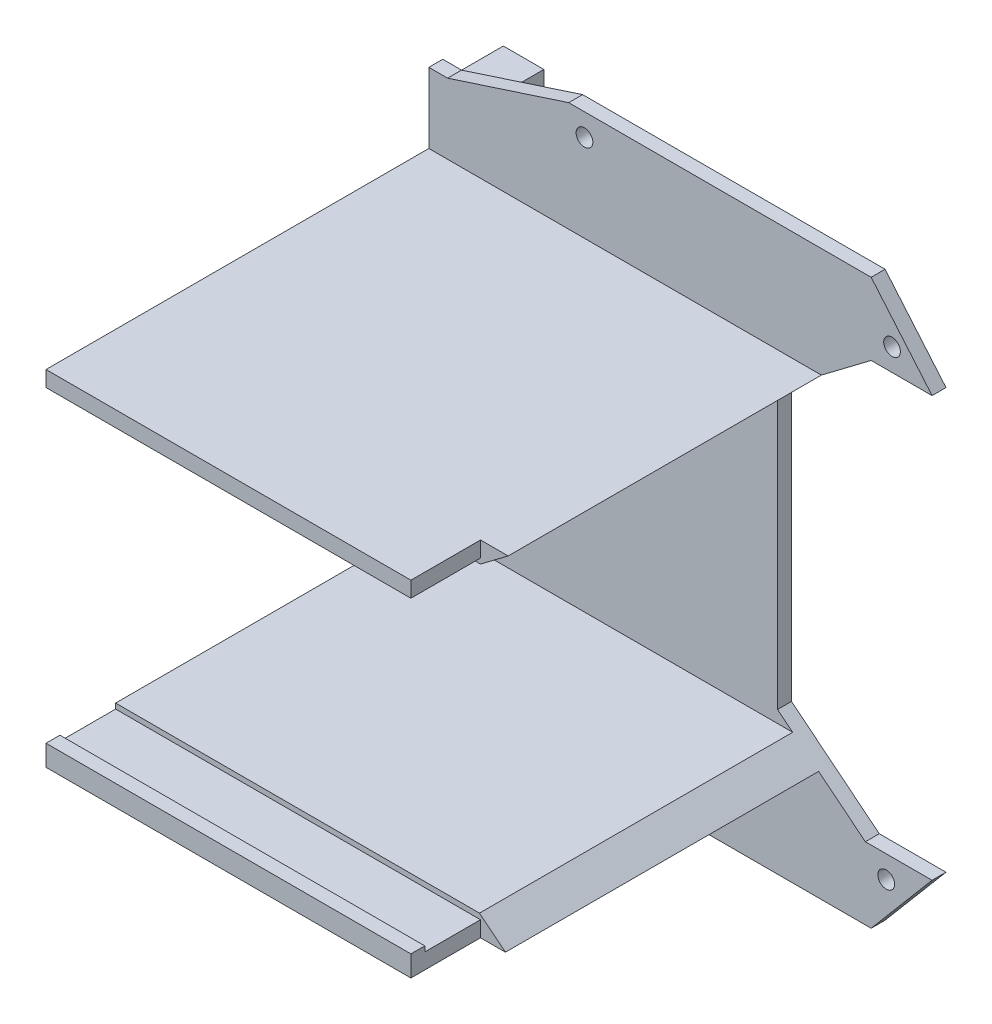
SolidWorks part; units mm, degrees
ref_plane "前视基准面" through (0, 0, 0) normal (0, 0, 1) x (1, 0, 0)
ref_plane "上视基准面" through (0, 0, 0) normal (0, 1, 0) x (1, 0, 0)
ref_plane "右视基准面" through (0, 0, 0) normal (1, 0, 0) x (0, 0, -1)
other "Configuration Table"
sketch "草图1" plane through (0, 0, 0) normal (0, 0, 1) x (1, 0, 0)
  line L0 (-117.8959, 10.15) -> (-117.8959, 50.15) construction
  line L1 (-117.8959, 10.15) -> (-117.8959, 50.15)
  line L3 (-104.45, 60.3) -> (-117.8959, 50.15)
  line L4 (-117.8959, 10.15) -> (-105.2853, 0)
  line L5 (-165.3, 65) -> (-168, 65)
  line L6 (-168, 65) -> (-168, -4.7)
  line L11 (-104.45, 68.85) -> (-104.45, 60.3)
  line L12 (-104.45, 60.3) -> (-95.7, 60.3)
  line L13 (-95.7, 60.3) -> (-104.45, 70.65)
  line L14 (-104.45, 70.65) -> (-147.9, 70.65)
  line L15 (-147.9, 70.65) -> (-165.3, 65)
  line L16 (-165.3, 65) -> (-159.4717, 65)
  line L17 (-159.4717, 65) -> (-149.4421, 68.2567)
  line L18 (-149.4421, 68.2567) -> (-149.4421, 63.85)
  line L19 (-149.4421, 63.85) -> (-141.4421, 63.85)
  line L20 (-141.4421, 63.85) -> (-141.4421, 68.85)
  line L21 (-141.4421, 68.85) -> (-104.45, 68.85)
  line L22 (-104.45, 68.85) -> (-104.45, 60.3)
  line L23 (-104.45, 60.3) -> (-95.7, 60.3)
  line L24 (-95.7, 60.3) -> (-104.45, 70.65)
  line L25 (-104.45, 70.65) -> (-147.9, 70.65)
  line L26 (-147.9, 70.65) -> (-165.3, 65)
  line L27 (-165.3, 65) -> (-159.4717, 65)
  line L28 (-159.4717, 65) -> (-149.4421, 68.2567)
  line L29 (-149.4421, 68.2567) -> (-149.4421, 63.85)
  line L30 (-149.4421, 63.85) -> (-141.4421, 63.85)
  line L31 (-141.4421, 63.85) -> (-141.4421, 68.85)
  line L32 (-141.4421, 68.85) -> (-104.45, 68.85)
  line L36 (-141.1744, -8.55) -> (-145.1744, -14.55)
  line L37 (-145.1744, -14.55) -> (-161.298, -14.55)
  line L38 (-161.298, -14.55) -> (-164.1652, -8.55)
  line L39 (-164.1652, -8.55) -> (-165.3, -8.55)
  line L40 (-165.3, -8.55) -> (-165.3, -4.7)
  line L41 (-165.3, -4.7) -> (-168, -4.7)
  line L42 (-168, -4.7) -> (-162.4327, -16.35)
  line L43 (-162.4327, -16.35) -> (-141.1744, -16.35)
  line L44 (-141.1744, -16.35) -> (-137.1744, -10.35)
  line L45 (-137.1744, -10.35) -> (-104.45, -10.35)
  line L46 (-104.45, -10.35) -> (-95.7, 0)
  line L47 (-95.7, 0) -> (-105.2853, 0)
  line L48 (-105.2853, 0) -> (-105.2853, -8.55)
  line L49 (-105.2853, -8.55) -> (-141.1744, -8.55)
  line L50 (-141.1744, -8.55) -> (-145.1744, -14.55)
  line L51 (-145.1744, -14.55) -> (-161.298, -14.55)
  line L52 (-161.298, -14.55) -> (-164.1652, -8.55)
  line L53 (-164.1652, -8.55) -> (-165.3, -8.55)
  line L54 (-165.3, -8.55) -> (-165.3, -4.7)
  line L55 (-165.3, -4.7) -> (-168, -4.7)
  line L56 (-168, -4.7) -> (-162.4327, -16.35)
  line L57 (-162.4327, -16.35) -> (-141.1744, -16.35)
  line L58 (-141.1744, -16.35) -> (-137.1744, -10.35)
  line L59 (-137.1744, -10.35) -> (-104.45, -10.35)
  line L60 (-104.45, -10.35) -> (-95.7, 0)
  line L61 (-95.7, 0) -> (-105.2853, 0)
  line L62 (-105.2853, 0) -> (-105.2853, -8.55)
  line L63 (-105.2853, -8.55) -> (-141.1744, -8.55)
  circle A0 centre (-145.6421, 67.45) radius 1.2 construction
  circle A1 centre (-145.6421, 67.45) radius 1.2
  circle A2 centre (-101.45, 63.5) radius 1.2 construction
  circle A3 centre (-101.45, 63.5) radius 1.2
  circle A4 centre (-102.2853, -3.2) radius 1.2 construction
  circle A5 centre (-102.2853, -3.2) radius 1.2
  circle A6 centre (-140.9744, -12.15) radius 1.2 construction
  circle A7 centre (-140.9744, -12.15) radius 1.2
  dimension "D1" = 0
  dimension "D2" = 0
extrude "凸台-拉伸1" add sketch "草图1" along normal blind 2 contours L63 L62 L4 L1 L3 L22 L32 L31 L30 L29 L28 L27 L5 L6 L55 L54 L53 L52 L51 L50 | L31 L32 L22 L23 L24 L25 L26 L27 L28 L29 L30 A3 A1 | L62 L63 L50 L51 L52 L53 L54 L55 L56 L57 L58 L59 L60 L61 A7 A5
sketch "草图2" plane through (0, 0, 0) normal (0, 0, -1) x (-1, 0, 0)
  line L0 (165.3, 65) -> (165.3, 59) construction
  line L1 (165.3, 65) -> (165.3, 59)
  line L2 (165.3, 1.3) -> (165.3, -4.7) construction
  line L3 (165.3, 1.3) -> (165.3, -4.7)
  line L4 (165.3, 59) -> (150.9, 59) construction
  line L5 (165.3, 59) -> (150.9, 59)
  line L6 (165.3, 1.3) -> (150.9, 1.3) construction
  line L7 (165.3, 1.3) -> (150.9, 1.3)
  line L8 (165.3, 59) -> (150.9, 59)
  line L10 (165.3, 65) -> (159.4717, 65)
  line L11 (165.3, 65) -> (165.3, 59)
  line L12 (165.3, 59) -> (159.4717, 59)
  line L13 (159.4717, 65) -> (159.4717, 59)
  line L14 (165.3, 1.3) -> (159.4717, 1.3)
  line L15 (104.45, 60.3) -> (117.8959, 50.15)
  line L16 (117.8959, 50.15) -> (117.8959, 10.15)
  line L17 (117.8959, 10.15) -> (105.2853, 0)
  line L18 (105.2853, 0) -> (95.7, 0)
  line L19 (95.7, 0) -> (104.45, -10.35)
  line L20 (104.45, -10.35) -> (137.1744, -10.35)
  line L21 (137.1744, -10.35) -> (141.1744, -16.35)
  line L22 (141.1744, -16.35) -> (162.4327, -16.35)
  line L23 (162.4327, -16.35) -> (168, -4.7)
  line L24 (168, -4.7) -> (168, 65)
  line L25 (168, 65) -> (165.3, 65)
  line L26 (165.3, 65) -> (147.9, 70.65)
  line L27 (147.9, 70.65) -> (104.45, 70.65)
  line L28 (104.45, 70.65) -> (95.7, 60.3)
  line L29 (95.7, 60.3) -> (104.45, 60.3)
  line L30 (104.45, 60.3) -> (117.8959, 50.15)
  line L31 (117.8959, 50.15) -> (117.8959, 10.15)
  line L32 (117.8959, 10.15) -> (105.2853, 0)
  line L33 (105.2853, 0) -> (95.7, 0)
  line L34 (95.7, 0) -> (104.45, -10.35)
  line L35 (104.45, -10.35) -> (137.1744, -10.35)
  line L36 (137.1744, -10.35) -> (141.1744, -16.35)
  line L37 (141.1744, -16.35) -> (162.4327, -16.35)
  line L38 (162.4327, -16.35) -> (168, -4.7)
  line L39 (168, -4.7) -> (168, 65)
  line L40 (168, 65) -> (165.3, 65)
  line L41 (165.3, 65) -> (147.9, 70.65)
  line L42 (147.9, 70.65) -> (104.45, 70.65)
  line L43 (104.45, 70.65) -> (95.7, 60.3)
  line L44 (95.7, 60.3) -> (104.45, 60.3)
  line L45 (165.3, 1.3) -> (165.3, -4.7)
  line L46 (165.3, -4.7) -> (159.4717, -4.7)
  line L47 (159.4717, 1.3) -> (159.4717, -4.7)
  dimension "D1" = 0
extrude "凸台-拉伸3" add sketch "草图2" along normal blind 6 contours L10 L13 L5 L1 | L7 L47 L46 L3
sketch "草图4" plane through (-165.3, 0, 0) normal (-1, 0, 0) x (0, 0, 1)
  circle A0 centre (-3.1, 61.9) radius 1.5 construction
  circle A1 centre (-3.1, 61.9) radius 1.5
  circle A2 centre (-3.1, -1.6) radius 1.5 construction
  circle A3 centre (-3.1, -1.6) radius 1.5
extrude "切除-拉伸1" cut sketch "草图4" against normal up to surface (5.8283 mm away) up to face at (-159.4717, -1.7, -3)
sketch "草图5" plane through (0, 0, 2) normal (0, 0, 1) x (1, 0, 0)
  line L0 (-223, 54.9) -> (-113, 54.9)
  line L1 (-223, 8.4) -> (-113, 8.4)
  line L2 (-223, 8.4) -> (-223, 51.9)
  line L3 (-223, 51.9) -> (-113, 51.9)
  line L4 (-113, 8.4) -> (-113, 51.9)
  line L5 (-223, 8.4) -> (-113, 51.9) construction
  line L6 (-223, 51.9) -> (-113, 8.4) construction
  line L7 (-223, 5.4) -> (-113, 5.4)
  line L8 (-113, 54.9) -> (-111.6035, 54.9)
  line L9 (-113, 5.4) -> (-111.9944, 5.4)
  line L15 (-117.8959, 50.15) -> (-104.45, 60.3)
  line L16 (-104.45, 60.3) -> (-95.7, 60.3)
  line L17 (-95.7, 60.3) -> (-104.45, 70.65)
  line L18 (-104.45, 70.65) -> (-147.9, 70.65)
  line L19 (-147.9, 70.65) -> (-165.3, 65)
  line L20 (-165.3, 65) -> (-168, 65)
  line L21 (-168, 65) -> (-168, -4.7)
  line L22 (-168, -4.7) -> (-162.4327, -16.35)
  line L23 (-162.4327, -16.35) -> (-141.1744, -16.35)
  line L24 (-141.1744, -16.35) -> (-137.1744, -10.35)
  line L25 (-137.1744, -10.35) -> (-104.45, -10.35)
  line L26 (-104.45, -10.35) -> (-95.7, 0)
  line L27 (-95.7, 0) -> (-105.2853, 0)
  line L28 (-105.2853, 0) -> (-117.8959, 10.15)
  line L29 (-117.8959, 10.15) -> (-117.8959, 50.15)
  line L30 (-117.8959, 50.15) -> (-104.45, 60.3)
  line L31 (-104.45, 60.3) -> (-95.7, 60.3)
  line L32 (-95.7, 60.3) -> (-104.45, 70.65)
  line L33 (-104.45, 70.65) -> (-147.9, 70.65)
  line L34 (-147.9, 70.65) -> (-165.3, 65)
  line L35 (-165.3, 65) -> (-168, 65)
  line L36 (-168, 65) -> (-168, -4.7)
  line L37 (-168, -4.7) -> (-162.4327, -16.35)
  line L38 (-162.4327, -16.35) -> (-141.1744, -16.35)
  line L39 (-141.1744, -16.35) -> (-137.1744, -10.35)
  line L40 (-137.1744, -10.35) -> (-104.45, -10.35)
  line L41 (-104.45, -10.35) -> (-95.7, 0)
  line L42 (-95.7, 0) -> (-105.2853, 0)
  line L43 (-105.2853, 0) -> (-117.8959, 10.15)
  line L44 (-117.8959, 10.15) -> (-117.8959, 50.15)
  point P2 (-168, 30.15)
  line M20 (-117.8959, 50.15) -> (-104.45, 60.3)
  line M26 (-168, 65) -> (-168, -4.7)
  line M33 (-105.2853, 0) -> (-117.8959, 10.15)
  dimension "D2" = 43.5
  dimension "D3" = 110
  dimension "D1" = 0
  dimension "D4" = 3
  dimension "D5" = 3
extrude "凸台-拉伸4" add sketch "草图5" along normal blind 45 contours L8 L0 L3 M26 M20 | L7 L9 L1 M33 M26
sketch "草图6" plane through (-168, 0, 0) normal (-1, 0, 0) x (0, 0, 1)
  line L0 (47, 51.9) -> (47, 8.4)
  line L2 (39, 7.65) -> (55, 7.65)
  line L3 (39, 7.65) -> (39, 52.65)
  line L4 (39, 52.65) -> (55, 52.65)
  line L5 (55, 7.65) -> (55, 52.65)
  line L6 (39, 7.65) -> (55, 52.65) construction
  line L7 (39, 52.65) -> (55, 7.65) construction
  line L8 (47, 54.9) -> (57, 54.9)
  line L9 (47, 54.9) -> (47, 52.65)
  line L10 (47, 52.65) -> (57, 52.65)
  line L11 (57, 54.9) -> (57, 52.65)
  line L12 (0, 65) -> (0, -4.7)
  line L13 (0, -4.7) -> (2, -4.7)
  line L14 (2, -4.7) -> (2, 5.4)
  line L15 (2, 5.4) -> (47, 5.4)
  line L16 (47, 5.4) -> (47, 8.4)
  line L17 (47, 8.4) -> (2, 8.4)
  line L18 (2, 8.4) -> (2, 51.9)
  line L19 (2, 51.9) -> (47, 51.9)
  line L20 (47, 51.9) -> (47, 54.9)
  line L21 (47, 54.9) -> (2, 54.9)
  line L22 (2, 54.9) -> (2, 65)
  line L23 (2, 65) -> (0, 65)
  line L24 (0, 65) -> (0, -4.7)
  line L25 (0, -4.7) -> (2, -4.7)
  line L26 (2, -4.7) -> (2, 5.4)
  line L27 (2, 5.4) -> (47, 5.4)
  line L28 (47, 5.4) -> (47, 8.4)
  line L29 (47, 8.4) -> (2, 8.4)
  line L30 (2, 8.4) -> (2, 51.9)
  line L31 (2, 51.9) -> (47, 51.9)
  line L32 (47, 51.9) -> (47, 54.9)
  line L33 (47, 54.9) -> (2, 54.9)
  line L34 (2, 54.9) -> (2, 65)
  line L35 (2, 65) -> (0, 65)
  line L36 (47, 5.4) -> (57, 5.4)
  line L37 (47, 5.4) -> (47, 8.4)
  line L38 (47, 8.4) -> (57, 8.4)
  line L39 (57, 5.4) -> (57, 8.4)
  point P2 (47, 30.15)
  line M21 (47, 5.4) -> (47, 8.4)
  line M25 (47, 51.9) -> (47, 54.9)
  dimension "D2" = 45
  dimension "D3" = 16
  dimension "D4" = 10
  dimension "D5" = 10
  dimension "D1" = 0
extrude "凸台-拉伸5" add sketch "草图6" against normal up to vertex (52.4223 mm away) contours L11 L8 L4 L10 M25 | L36 L39 L38 L5 L2 M21
